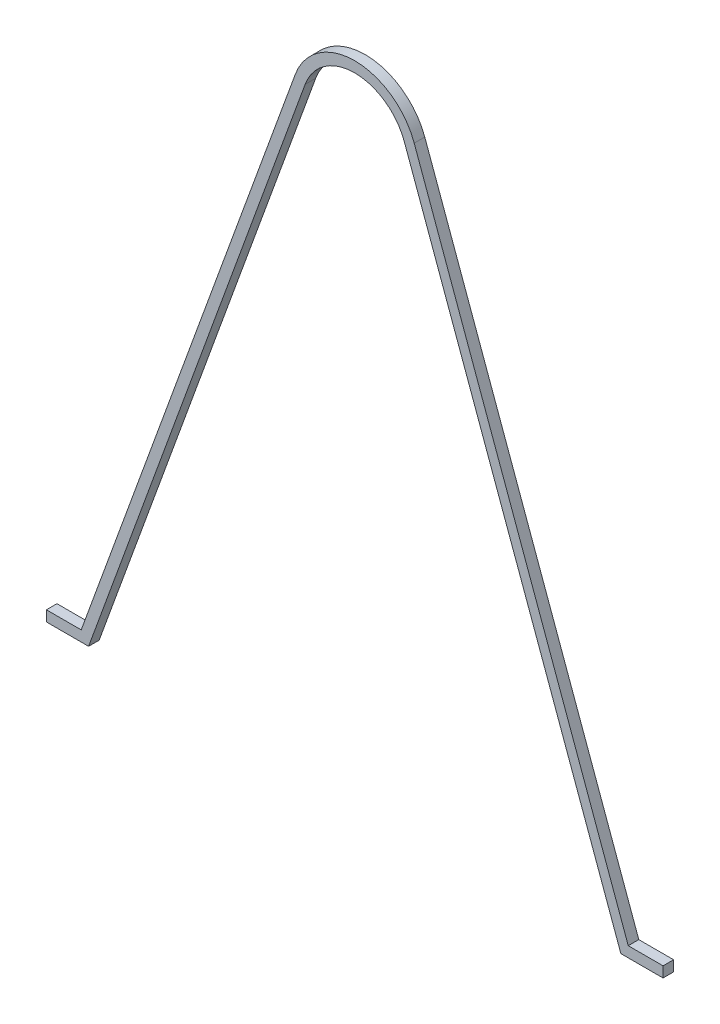
SolidWorks part; units mm, degrees
ref_plane "Front" through (0, 0, 0) normal (0, 0, 1) x (1, 0, 0)
ref_plane "Top" through (0, 0, 0) normal (0, 1, 0) x (1, 0, 0)
ref_plane "Right" through (0, 0, 0) normal (1, 0, 0) x (0, 0, -1)
sketch "Эскиз1" plane through (0, 0, 0) normal (0, 0, 1) x (1, 0, 0)
  line L0 (-292.1967, -546.7146) -> (-252.1967, -546.7146)
  line L1 (-252.1967, -546.7146) -> (-46.9846, 17.101)
  line L2 (292.1967, -546.7146) -> (252.1967, -546.7146)
  line L3 (252.1967, -546.7146) -> (46.9846, 17.101)
  line L4 (292.1967, -536.7146) -> (259.1988, -536.7146)
  line L5 (259.1988, -536.7146) -> (56.3816, 20.5212)
  line L6 (-259.1988, -536.7146) -> (-56.3816, 20.5212)
  line L7 (-292.1967, -536.7146) -> (-259.1988, -536.7146)
  line L8 (-292.1967, -536.7146) -> (-292.1967, -546.7146)
  line L9 (292.1967, -536.7146) -> (292.1967, -546.7146)
  arc A0 (46.9846, 17.101) -> (-46.9846, 17.101) centre (0, 0) ccw
  arc A1 (56.3816, 20.5212) -> (-56.3816, 20.5212) centre (0, 0) ccw
  dimension "D4" = 50
  dimension "D1" = 40
  dimension "D2" = 600
  dimension "D3" = 110
  dimension "D5" = 10
extrude "Бобышка-Вытянуть1" add sketch "Эскиз1" along normal blind 10
